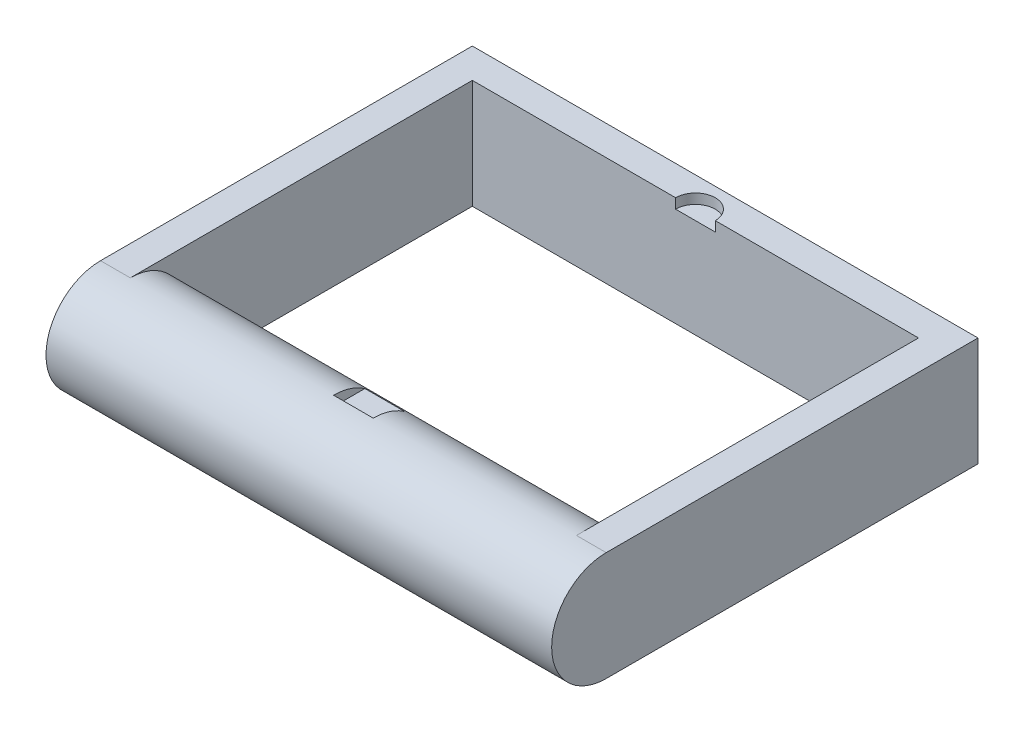
SolidWorks part; units mm, degrees
material "Zinc AC41A Alloy, As Cast"
ref_plane "Front Plane" through (0, 0, 0) normal (0, 0, 1) x (1, 0, 0)
ref_plane "Top Plane" through (0, 0, 0) normal (0, 1, 0) x (1, 0, 0)
ref_plane "Right Plane" through (0, 0, 0) normal (1, 0, 0) x (0, 0, -1)
sketch "Sketch1" plane through (0, 0, 0) normal (1, 0, 0) x (0, 0, -1)
  circle A0 centre (0, 0) radius 2.75
  dimension "D1" = 5.5
extrude "Boss-Extrude1" add sketch "Sketch1" along normal blind 22.5
sketch "Sketch2" plane through (0, 0, 0) normal (-1, 0, 0) x (0, 0, 1)
  line L1 (0, 2.75) -> (-17.25, 2.75)
  line L3 (0, -2.75) -> (-17.25, -2.75)
  line L4 (-17.25, 2.75) -> (-17.25, -2.75)
  arc A1 (0, -2.75) -> (0, 2.75) centre (0, 0) ccw
extrude "Boss-Extrude2" add sketch "Sketch2" along normal blind 1.5
sketch "Sketch3" plane through (22.5, 0, 0) normal (1, 0, 0) x (0, 0, -1)
  line L6 (0, -2.75) -> (17.25, -2.75)
  line L8 (0, 2.75) -> (17.25, 2.75)
  line L9 (17.25, -2.75) -> (17.25, 2.75)
  arc A0 (0, 2.75) -> (0, -2.75) centre (0, 0) ccw
extrude "Boss-Extrude3" add sketch "Sketch3" along normal blind 1.5
sketch "Sketch5" plane through (0, 0, -17.25) normal (0, 0, -1) x (-1, 0, 0)
  line L0 (1.5, 2.75) -> (1.5, -2.75) construction
  line L1 (-24, -2.75) -> (1.5, -2.75)
  line L2 (-24, -2.75) -> (-24, 2.75)
  line L3 (-24, 2.75) -> (1.5, 2.75)
  line L4 (1.5, -2.75) -> (1.5, 2.75)
  line L5 (1.5, 2.75) -> (0, 2.75) construction
extrude "Boss-Extrude4" add sketch "Sketch5" along normal blind 1.5
sketch "Sketch6" plane through (0, 2.75, 0) normal (0, 1, 0) x (1, 0, 0)
  line L0 (0, 17.25) -> (22.5, 17.25) construction
  line L10 (10.25, 17.25) -> (10.25, 0)
  line L11 (10.25, 0) -> (12.25, 0)
  line L12 (12.25, 17.25) -> (12.25, 0)
  arc A0 (10.25, 17.25) -> (12.25, 17.25) centre (11.25, 17.25) cw
  dimension "D1" = 2
extrude "Cut-Extrude1" cut sketch "Sketch6" against normal blind 0.5
